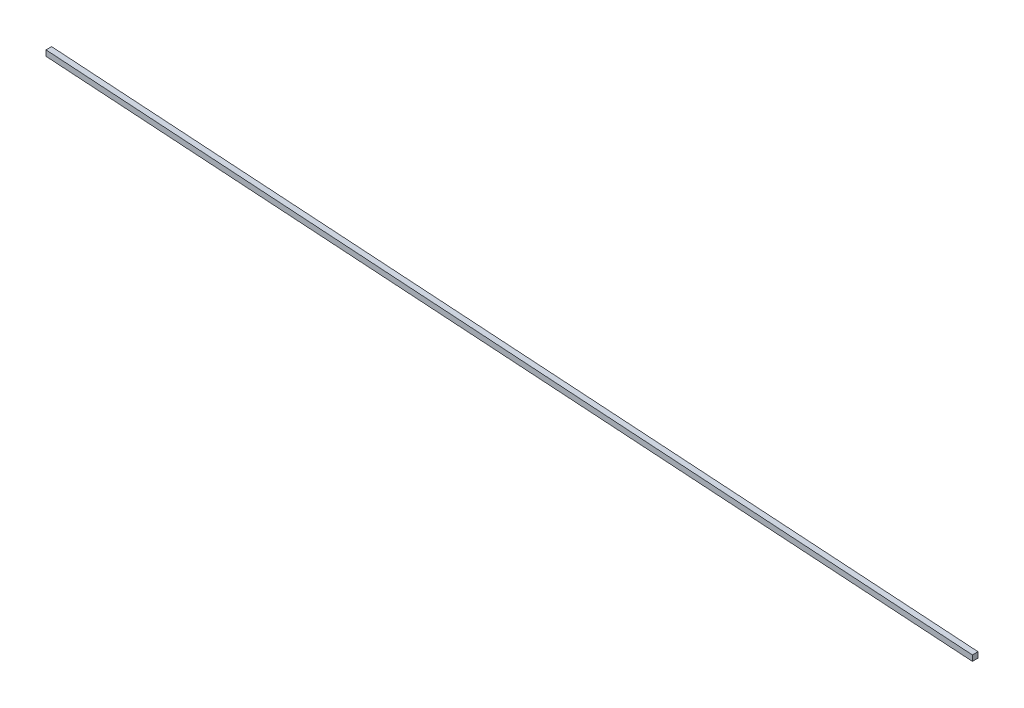
SolidWorks part; units mm, degrees
ref_plane "前视基准面" through (0, 0, 0) normal (0, 0, 1) x (1, 0, 0)
ref_plane "上视基准面" through (0, 0, 0) normal (0, 1, 0) x (1, 0, 0)
ref_plane "右视基准面" through (0, 0, 0) normal (1, 0, 0) x (0, 0, -1)
sketch "Model" plane through (0, 0, 0) normal (0, 0, 1) x (1, 0, 0)
  line L0 (8.8008, 36.0662) -> (503.8008, 3.5656)
  line L1 (8.8008, 33.0662) -> (503.8008, 0.5656)
  line L2 (8.8008, 36.0662) -> (8.8008, 33.0662)
  line L3 (503.8008, 3.5656) -> (503.8008, 0.5656)
extrude "凸台-拉伸1" add sketch "Model" along normal blind 3
